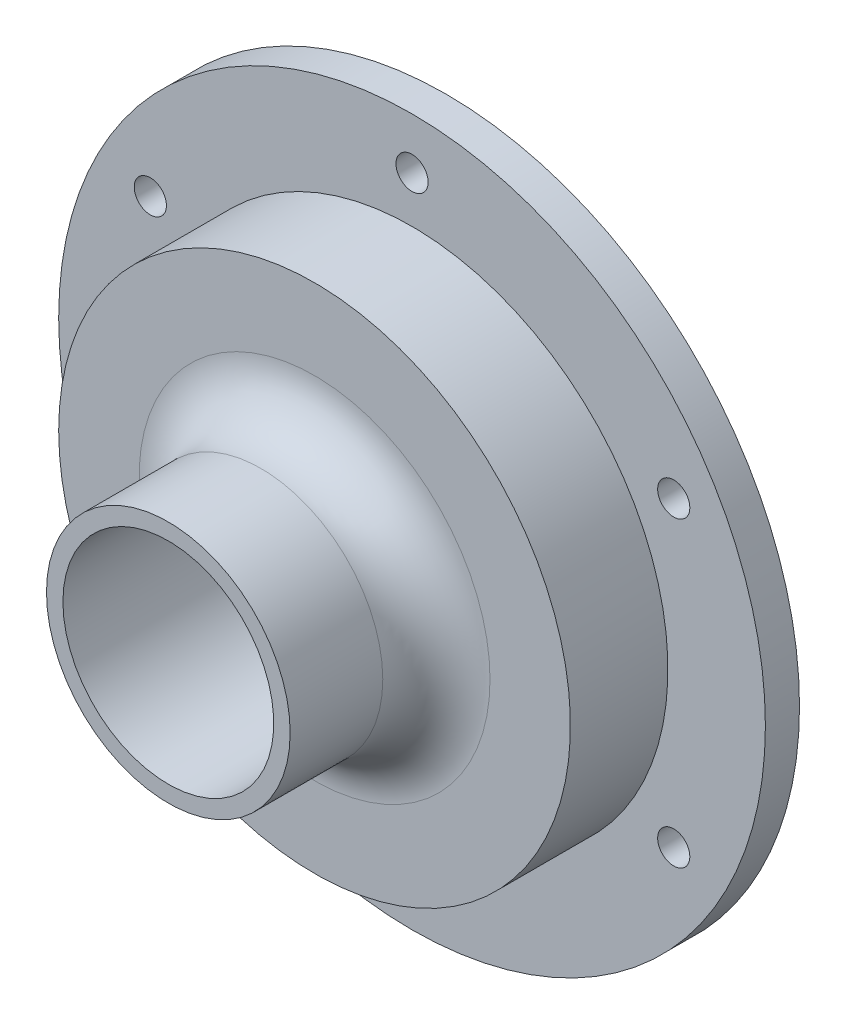
SolidWorks part; units mm, degrees
ref_plane "Front Plane" through (0, 0, 0) normal (0, 0, 1) x (1, 0, 0)
ref_plane "Top Plane" through (0, 0, 0) normal (0, 1, 0) x (1, 0, 0)
ref_plane "Right Plane" through (0, 0, 0) normal (1, 0, 0) x (0, 0, -1)
sketch "Sketch1" plane through (0, 0, 0) normal (0, 1, 0) x (1, 0, 0)
  line L0 (-72.5, 0) -> (72.5, 0) construction
  line L1 (-21.63, 0) -> (-72.5, 0)
  line L2 (-72.5, 0) -> (-72.5, -7)
  line L3 (-72.5, -7) -> (-52.5, -7)
  line L4 (-52.5, -7) -> (-52.5, -27)
  line L5 (-52.5, -27) -> (-25, -27)
  line L6 (-25, -27) -> (-25, -57)
  line L7 (-25, -57) -> (-21.63, -57)
  line L8 (-21.63, -57) -> (-21.63, 0)
  line L9 (0, 0) -> (0, -57) construction
  dimension "D1" = 145
  dimension "D2" = 21.63
  dimension "D3" = 25
  dimension "D4" = 7
  dimension "D5" = 20
  dimension "D6" = 30
  dimension "D7" = 20
revolve "Revolve1" add sketch "Sketch1" angle 360 about L9
fillet "Fillet1" radius 11 1 edges at (-25, 0, 27)
sketch "Sketch6" plane through (0, 0, 0) normal (0, 0, -1) x (-1, 0, 0)
  point P0 (0, 62)
  dimension "D1" = 62
hole_wizard "CBORE for M6 Hex Head Bolt1" positions "Sketch7" profile "Sketch8" counterbore size "M6" standard "ISO" end condition through all
sketch "Sketch7" plane through (0, 0, 0) normal (0, 0, -1) x (-1, 0, 0)
  point P0 (0, 62)
sketch "Sketch8" plane through (0, 62, 0) normal (1, 0, 0) x (0, 1, 0)
  line L0 (0, 0) -> (0, 57)
  line L1 (0, 57) -> (3.3, 57)
  line L3 (3.3, 57) -> (3.3, 1)
  line L4 (3.3, 1) -> (7.2735, 1)
  line L5 (7.2735, 1) -> (7.2735, 0)
  line L7 (7.2735, 0) -> (0, 0)
  line L11 (0, -6.35) -> (0, 107.95) construction
  dimension "Thru Hole Dia." = 6.6
  dimension "Thru Hole Depth" = 57
  dimension "C'Bore Dia." = 14.547
  dimension "C'Bore Depth" = 1
pattern_circular "CirPattern1" count 6 over 360 about axis through (0, 0, 0) along (0, 0, 1) of "CBORE for M6 Hex Head Bolt1"
